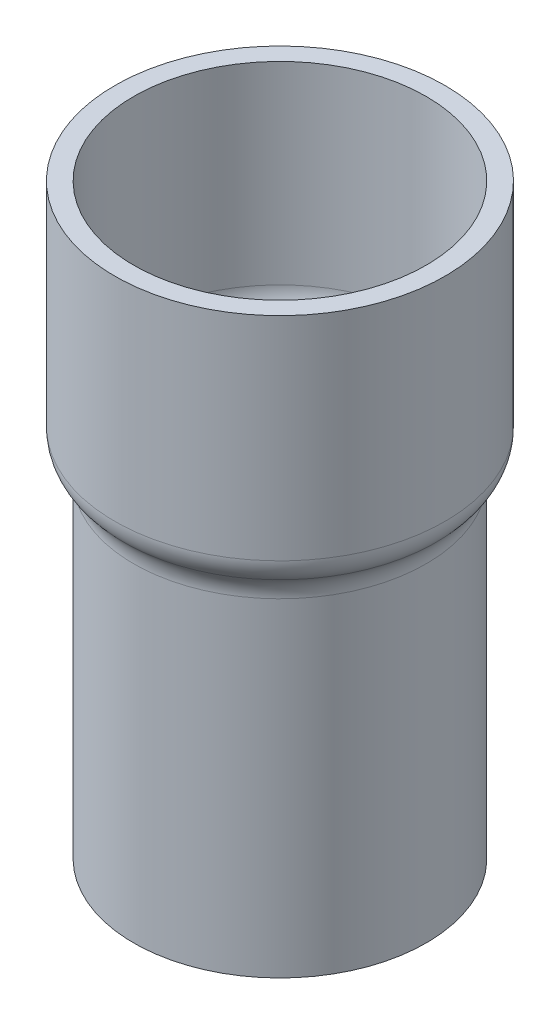
SolidWorks part; units mm, degrees
material "Brass"
ref_plane "Ön Düzlem" through (0, 0, 0) normal (0, 0, 1) x (1, 0, 0)
ref_plane "Üst Düzlem" through (0, 0, 0) normal (0, 1, 0) x (1, 0, 0)
ref_plane "Sağ Düzlem" through (0, 0, 0) normal (1, 0, 0) x (0, 0, -1)
sketch "Sketch1" plane through (0, 0, 0) normal (0, 0, 1) x (1, 0, 0)
  line L0 (-1.35, 0) -> (-1.35, 3.68)
  line L2 (-1.55, 4.1694) -> (-1.55, 6.22)
  line L3 (-1.55, 6.22) -> (-1.75, 6.22)
  line L4 (-1.75, 6.22) -> (-1.75, 3.9694)
  line L6 (-1.55, 3.48) -> (-1.55, 0)
  line L7 (-1.55, 0) -> (-1.35, 0)
  arc A0 (-1.6502, 3.7251) -> (-1.55, 3.48) centre (-1.9, 3.48) cw
  arc A1 (-1.6502, 3.7251) -> (-1.75, 3.9694) centre (-1.4013, 3.9694) cw
  arc A2 (-1.4502, 3.9251) -> (-1.35, 3.68) centre (-1.7, 3.68) cw
  arc A3 (-1.4502, 3.9251) -> (-1.55, 4.1694) centre (-1.2013, 4.1694) cw
  dimension "D4" = 0.35
  dimension "D5" = 3.9694
  dimension "D10" = 0.35
  dimension "D11" = 0.3487
  dimension "D1" = 1.55
  dimension "D2" = 6.22
  dimension "D3" = 3.48
  dimension "D6" = 1.55
  dimension "D7" = 1.35
  dimension "D8" = 1.75
  dimension "D9" = 3.68
ref_axis "Axis1" through (0, 0, 0) along (0, 1, 0)
revolve "Revolve1" add sketch "Sketch1" angle 360 about axis through (0, 0, 0) along (0, 1, 0)
